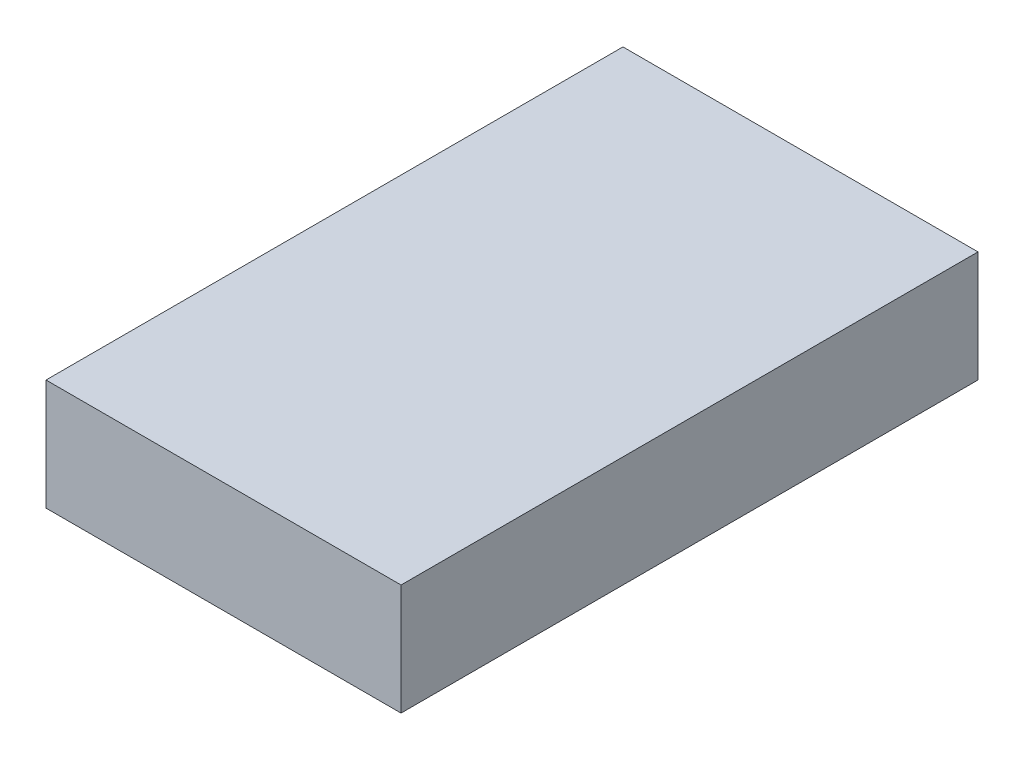
SolidWorks part; units mm, degrees
ref_plane "정면" through (0, 0, 0) normal (0, 0, 1) x (1, 0, 0)
ref_plane "윗면" through (0, 0, 0) normal (0, 1, 0) x (1, 0, 0)
ref_plane "우측면" through (0, 0, 0) normal (1, 0, 0) x (0, 0, -1)
sketch "스케치1" plane through (0, 0, 0) normal (0, 1, 0) x (1, 0, 0)
  line L1 (8, -13) -> (-8, -13)
  line L2 (8, -13) -> (8, 13)
  line L3 (8, 13) -> (-8, 13)
  line L4 (-8, -13) -> (-8, 13)
  line L5 (8, -13) -> (-8, 13) construction
  line L6 (8, 13) -> (-8, -13) construction
  point P0 (0, 0)
  dimension "D1" = 16
  dimension "D2" = 26
extrude "보스-돌출1" add sketch "스케치1" along normal blind 5
sketch "스케치3" plane through (0, 0, 0) normal (0, 1, 0) x (1, 0, 0)
  line L1 (0, 0) -> (-14, 0)
  line L2 (0, 0) -> (0, 25)
  line L3 (0, 25) -> (-14, 25)
  line L4 (-14, 0) -> (-14, 25)
  dimension "D1" = 14
  dimension "D2" = 25
